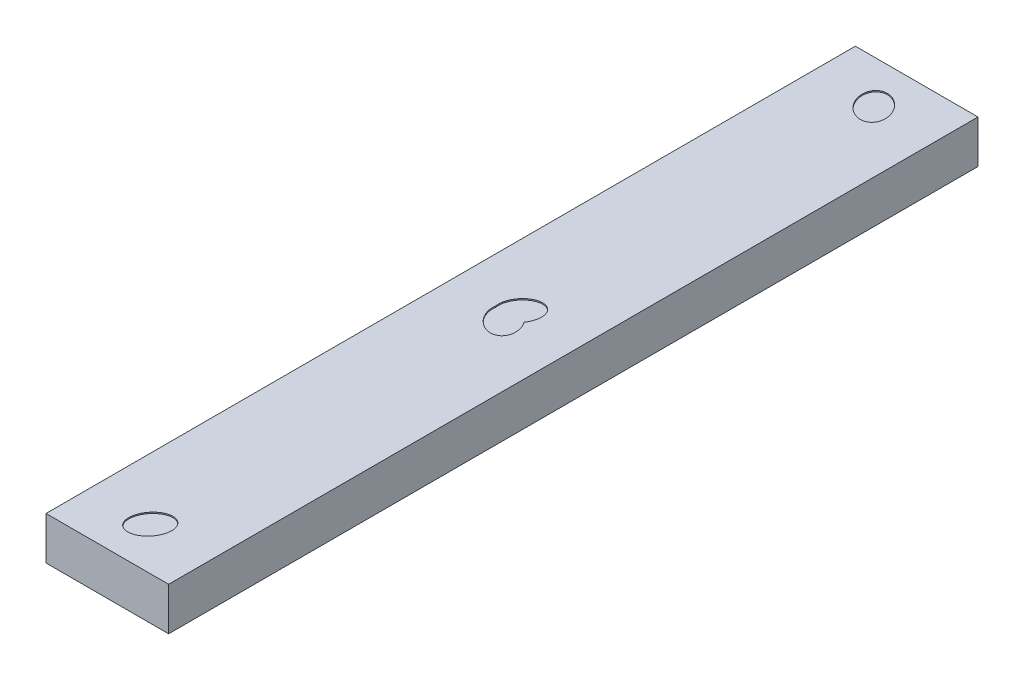
SolidWorks part; units mm, degrees
ref_plane "Alzado" through (0, 0, 0) normal (0, 0, 1) x (1, 0, 0)
ref_plane "Planta" through (0, 0, 0) normal (0, 1, 0) x (1, 0, 0)
ref_plane "Vista lateral" through (0, 0, 0) normal (1, 0, 0) x (0, 0, -1)
sketch "Croquis1" plane through (0, 0, 0) normal (0, 1, 0) x (1, 0, 0)
  line L1 (-10, -66) -> (10, -66)
  line L2 (-10, -66) -> (-10, 66)
  line L3 (-10, 66) -> (10, 66)
  line L4 (10, -66) -> (10, 66)
  line L5 (-10, -66) -> (10, 66) construction
  line L6 (-10, 66) -> (10, -66) construction
  point P0 (0, 0)
  dimension "D1" = 20
  dimension "D2" = 132
extrude "Saliente-Extruir1" add sketch "Croquis1" along normal blind 7
sketch "Croquis2" plane through (0, 7, 0) normal (0, 1, 0) x (1, 0, 0)
  line L0 (-10, 0) -> (10, 0) construction
  line L1 (-10, 66) -> (-10, -66) construction
  line L2 (10, -66) -> (10, 66) construction
  line L3 (-9.9997, -0.0002) -> (10.0003, -0.0002)
  line L4 (0, -66) -> (0, 66) construction
  line L5 (-10, -66) -> (10, -66) construction
  line L6 (10, 66) -> (-10, 66) construction
  ellipse E0 centre (0.0003, 1.3093) end of major axis (1.8603, 3.9132) minor radius 2.375
  ellipse E1 centre (0.0003, -1.3096) end of major axis (1.8603, -3.9136) minor radius 2.375
  ellipse E2 centre (0.008, -59) end of major axis (-1.852, -61.6039) minor radius 2.375
  ellipse E4 centre (0.008, 58.9996) end of major axis (1.868, 56.3957) minor radius 2.375
  point P8 (0.0003, -0.0002)
  dimension "D1" = 6.4
  dimension "D2" = 4.75
  dimension "D3" = 7
extrude "Cortar-Extruir1" cut sketch "Croquis2" against normal blind 0.2 contours E2 | E0 E1 | E1 E0 | E4
